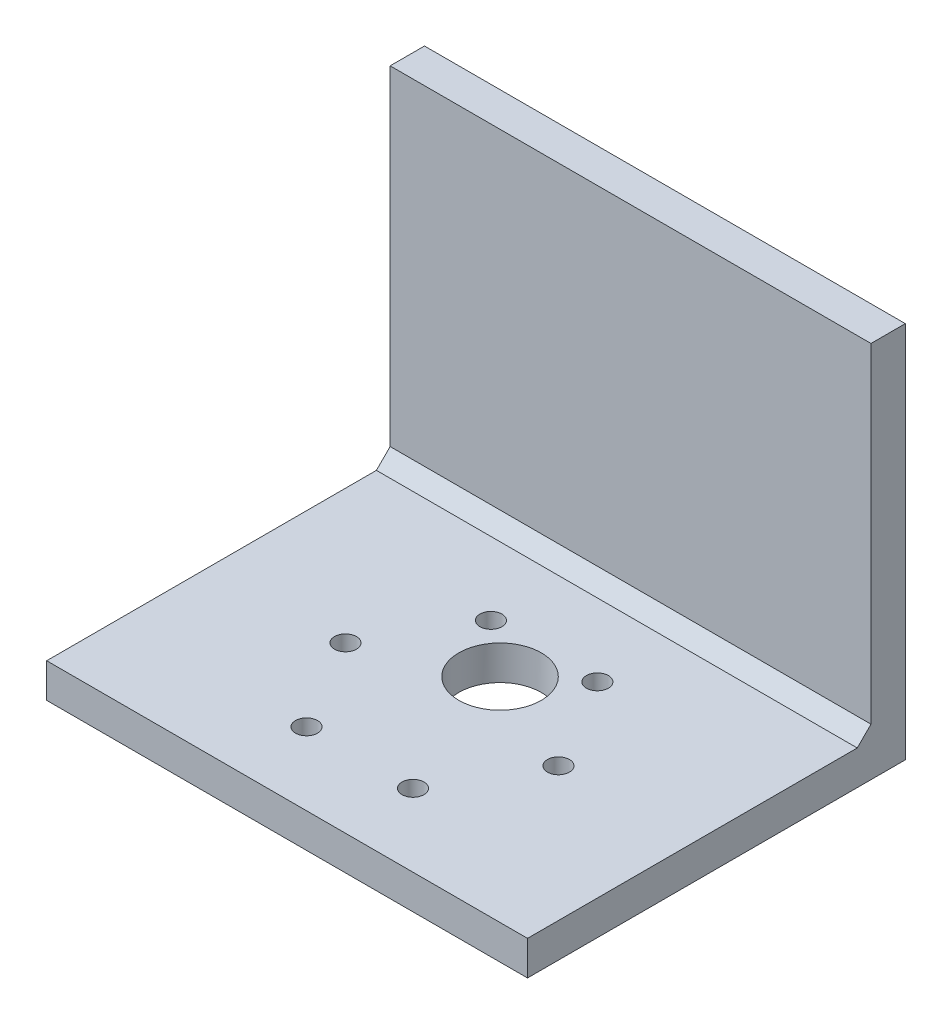
SolidWorks part; units mm, degrees
ref_plane "Płaszczyzna przednia" through (0, 0, 0) normal (0, 0, 1) x (1, 0, 0)
ref_plane "Płaszczyzna górna" through (0, 0, 0) normal (0, 1, 0) x (1, 0, 0)
ref_plane "Płaszczyzna prawa" through (0, 0, 0) normal (1, 0, 0) x (0, 0, -1)
sketch "Szkic2" plane through (0, 0, 0) normal (0, 1, 0) x (1, 0, 0)
  line L1 (-35, -25) -> (35, -25)
  line L2 (-35, -25) -> (-35, 25)
  line L3 (-35, 25) -> (35, 25)
  line L4 (35, -25) -> (35, 25)
  line L5 (0, 25) -> (0, -25) construction
  line L6 (-35, 0) -> (35, 0) construction
  point P0 (0, 0)
  dimension "D1" = 50
  dimension "D2" = 70
extrude "Dodanie-wyciągnięcie1" add sketch "Szkic2" along normal blind 5
sketch "Szkic3" plane through (0, 5, 0) normal (0, 1, 0) x (1, 0, 0)
  point P0 (-7.75, -14.4234)
  point P1 (7.75, -14.4234)
  point P3 (15.5, -1)
  point P5 (7.75, 12.4234)
  point P7 (-7.75, 12.4234)
  point P9 (-15.5, -1)
sketch "Szkic5" plane through (0, 5, 0) normal (0, 1, 0) x (1, 0, 0)
  point P0 (-7.75, -14.4234)
  point P3 (7.75, -14.4234)
  point P6 (15.5, -1)
  point P9 (7.75, 12.4234)
  point P12 (-7.75, 12.4234)
  point P15 (-15.5, -1)
hole_wizard "Otwór Ø3.2 (3.2)1" positions "Szkic5" profile "Szkic6" hole size "Ø3.2" standard "DIN"
sketch "Szkic6" plane through (-7.75, 5, 14.4234) normal (1, 0, 0) x (0, 0, 1)
  line L0 (0, 0) -> (0, 5.9614)
  line L1 (0, 5.9614) -> (1.6, 5)
  line L2 (1.6, 5) -> (1.6, 0)
  line L5 (1.6, 0) -> (0, 0)
  line L10 (0, 5.9614) -> (-1.6, 5) construction
  line L11 (0, -6.35) -> (0, 107.95) construction
  dimension "Średnica otworu" = 3.2
  dimension "Głębokość otworu" = 5
  dimension "Kąt wiertła" = 118
sketch "Szkic7" plane through (0, 5, 0) normal (0, 1, 0) x (1, 0, 0)
  circle A0 centre (0, 6) radius 6
extrude "Wytnij-wyciągnięcie1" cut sketch "Szkic7" against normal up to next
sketch "Szkic8" plane through (0, 0, -25) normal (0, 0, -1) x (-1, 0, 0)
  line L2 (-35, 5) -> (-35, 55)
  line L3 (-35, 55) -> (35, 55)
  line L4 (35, 5) -> (35, 55)
  line L5 (0, 55) -> (0, 5) construction
  line L6 (-35, 30) -> (35, 30) construction
  line L8 (-35, 5) -> (-35, 0)
  line L9 (-35, 0) -> (35, 0)
  line L10 (35, 5) -> (35, 0)
  line L11 (0, 0) -> (0, 5) construction
  line L12 (-35, 2.5) -> (35, 2.5) construction
  point P258 (0, 2.5)
  point P448 (0, 30)
  dimension "D1" = 55
extrude "Dodanie-wyciągnięcie2" add sketch "Szkic8" along normal blind 5
chamfer "Sfazowanie1" distance 2 angle 45 1 edges at (0, 5, -25)
